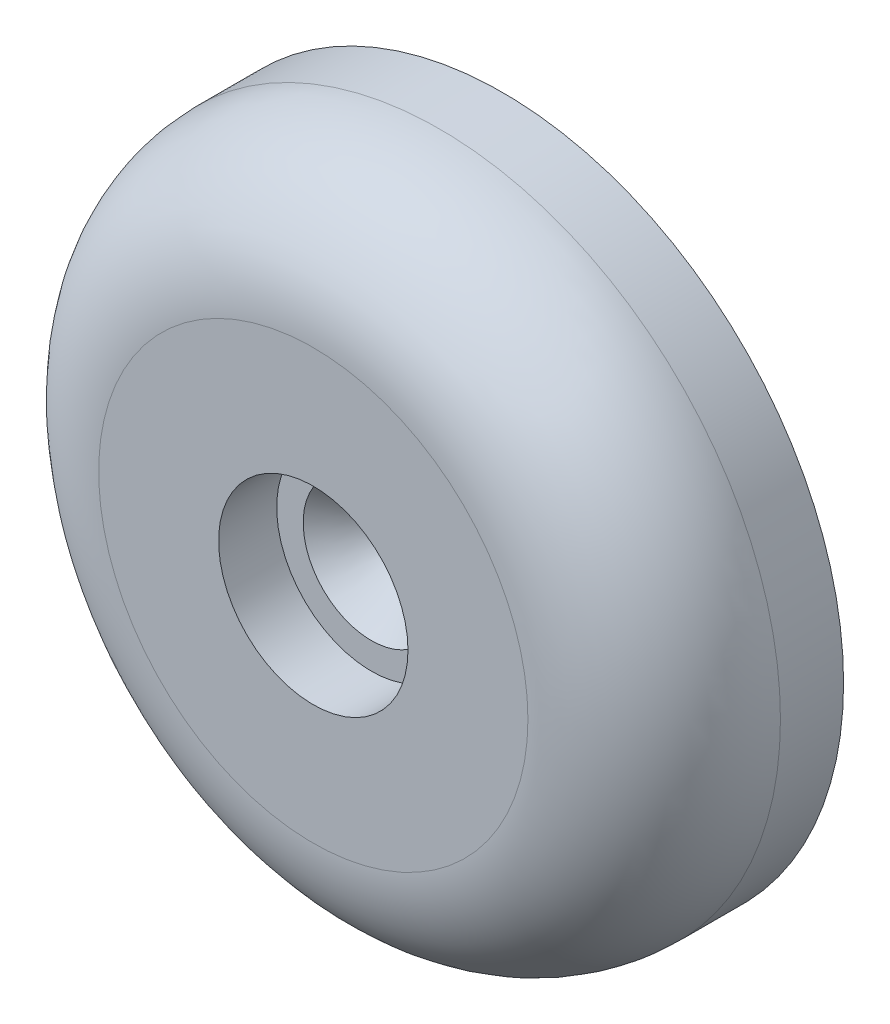
SolidWorks part; units mm, degrees
ref_plane "Спереди" through (0, 0, 0) normal (0, 0, 1) x (1, 0, 0)
ref_plane "Сверху" through (0, 0, 0) normal (0, 1, 0) x (1, 0, 0)
ref_plane "Справа" through (0, 0, 0) normal (1, 0, 0) x (0, 0, -1)
other "Configuration Table"
sketch "Эскиз2" plane through (0, 0, 0) normal (0, 0, 1) x (1, 0, 0)
  circle A0 centre (0, 0) radius 27
  dimension "D1" = 54
extrude "Бобышка-Вытянуть1" add sketch "Эскиз2" along normal blind 15
fillet "Скругление3" radius 10 1 edges at (27, 0, 15)
shell "Оболочка2" thickness 2
sketch "Эскиз5" plane through (0, 0, 13) normal (0, 0, -1) x (-1, 0, 0)
  circle A0 centre (0, 0) radius 9.5
  dimension "D1" = 19
extrude "Бобышка-Вытянуть2" add sketch "Эскиз5" along normal blind 13
sketch "Эскиз6" plane through (0, 0, 0) normal (0, 0, -1) x (-1, 0, 0)
  circle A0 centre (0, 0) radius 2.4
  dimension "D1" = 4.8
extrude "Вырез-Вытянуть1" cut sketch "Эскиз6" against normal through all
sketch "Эскиз7" plane through (0, 0, 0) normal (0, 0, -1) x (-1, 0, 0)
  line L0 (0, 29.4416) -> (0, -31.5446) construction
  line L1 (-0.6, 9) -> (-0.6, 26)
  line L2 (-0.6, 26) -> (0.6, 26)
  line L3 (0.6, 26) -> (0.6, 9)
  line L4 (0.6, 9) -> (-0.6, 9)
  line L5 (7.4942, 5.0196) -> (22.2167, 13.5196)
  line L6 (8.0942, 3.9804) -> (7.4942, 5.0196)
  line L7 (22.2167, 13.5196) -> (22.8167, 12.4804)
  line L8 (22.8167, 12.4804) -> (8.0942, 3.9804)
  line L9 (8.0942, -3.9804) -> (22.8167, -12.4804)
  line L10 (7.4942, -5.0196) -> (8.0942, -3.9804)
  line L11 (22.8167, -12.4804) -> (22.2167, -13.5196)
  line L12 (22.2167, -13.5196) -> (7.4942, -5.0196)
  line L13 (0.6, -9) -> (0.6, -26)
  line L14 (-0.6, -9) -> (0.6, -9)
  line L15 (0.6, -26) -> (-0.6, -26)
  line L16 (-0.6, -26) -> (-0.6, -9)
  line L17 (-7.4942, -5.0196) -> (-22.2167, -13.5196)
  line L18 (-8.0942, -3.9804) -> (-7.4942, -5.0196)
  line L19 (-22.2167, -13.5196) -> (-22.8167, -12.4804)
  line L20 (-22.8167, -12.4804) -> (-8.0942, -3.9804)
  line L21 (-8.0942, 3.9804) -> (-22.8167, 12.4804)
  line L22 (-7.4942, 5.0196) -> (-8.0942, 3.9804)
  line L23 (-22.8167, 12.4804) -> (-22.2167, 13.5196)
  line L24 (-22.2167, 13.5196) -> (-7.4942, 5.0196)
  circle A0 centre (0, 0) radius 27 construction
  point P32 (0, 0)
  dimension "D4" = 26
  dimension "D1" = 1.2
  dimension "D2" = 0.6
  dimension "D3" = 17
  dimension "D5" = 6
extrude "Бобышка-Вытянуть3" add sketch "Эскиз7" against normal up to body
sketch "Эскиз8" plane through (0, 0, 15) normal (0, 0, 1) x (1, 0, 0)
  circle A0 centre (0, 0) radius 7.5
  dimension "D1" = 15
extrude "Вырез-Вытянуть2" cut sketch "Эскиз8" against normal blind 4.6
chamfer "Фаска1" distance 3 angle 45 1 edges at (2.4, 0, 10.4)
